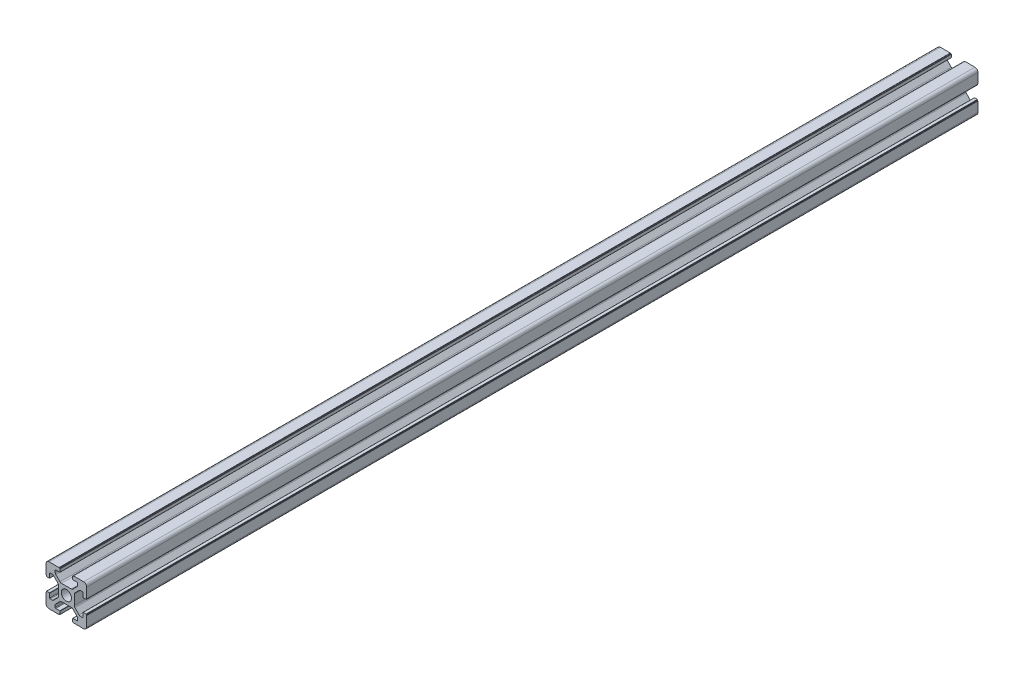
SolidWorks part; units mm, degrees
material "6063-T5"
ref_plane "前视基准面" through (0, 0, 0) normal (0, 0, 1) x (1, 0, 0)
ref_plane "上视基准面" through (0, 0, 0) normal (0, 1, 0) x (1, 0, 0)
ref_plane "右视基准面" through (0, 0, 0) normal (1, 0, 0) x (0, 0, -1)
sketch "草图1" plane through (0, 0, 0) normal (0, 0, 1) x (1, 0, 0)
  line L0 (-1.4389, 10) -> (24.3741, 10) construction
  line L1 (20, 13.6) -> (20, 20)
  line L2 (0, 0) -> (0, 6.4)
  line L3 (0, 20) -> (6.4, 20)
  line L4 (20, 0) -> (20, 6.4)
  line L5 (10, 21.5388) -> (10, -2.4017) construction
  line L6 (6.9, 18.3) -> (6.9, 19.7)
  line L7 (6.8, 18.2) -> (4.8, 18.2)
  line L8 (4.5, 17.9) -> (4.5, 16.9749)
  line L9 (4.7929, 16.2678) -> (6.8678, 14.1929)
  line L10 (7.5749, 13.9) -> (12.4251, 13.9)
  line L11 (6.8, 19.8) -> (6.4, 19.8)
  line L12 (6.4, 19.8) -> (6.4, 20)
  line L13 (0, 13.6) -> (0.2, 13.6)
  line L14 (0.2, 13.6) -> (0.2, 13.2)
  line L15 (0.3, 13.1) -> (1.7, 13.1)
  line L16 (1.8, 13.2) -> (1.8, 15.2)
  line L17 (2.1, 15.5) -> (3.0251, 15.5)
  line L18 (3.7322, 15.2071) -> (5.8071, 13.1322)
  line L19 (6.1, 12.4251) -> (6.1, 7.5749)
  line L20 (13.6, 19.8) -> (13.6, 20)
  line L21 (13.2, 19.8) -> (13.6, 19.8)
  line L22 (13.1, 18.3) -> (13.1, 19.7)
  line L23 (13.2, 18.2) -> (15.2, 18.2)
  line L24 (15.5, 17.9) -> (15.5, 16.9749)
  line L25 (15.2071, 16.2678) -> (13.1322, 14.1929)
  line L26 (0, 6.4) -> (0.2, 6.4)
  line L27 (0.2, 6.4) -> (0.2, 6.8)
  line L28 (0.3, 6.9) -> (1.7, 6.9)
  line L29 (1.8, 6.8) -> (1.8, 4.8)
  line L30 (2.1, 4.5) -> (3.0251, 4.5)
  line L31 (3.7322, 4.7929) -> (5.8071, 6.8678)
  line L32 (13.6, 20) -> (20, 20)
  line L33 (0, 13.6) -> (0, 20)
  line L34 (13.6, 0.2) -> (13.6, 0)
  line L35 (13.2, 0.2) -> (13.6, 0.2)
  line L36 (13.1, 1.7) -> (13.1, 0.3)
  line L37 (13.2, 1.8) -> (15.2, 1.8)
  line L38 (15.5, 2.1) -> (15.5, 3.0251)
  line L39 (15.2071, 3.7322) -> (13.1322, 5.8071)
  line L40 (4.5, 2.1) -> (4.5, 3.0251)
  line L41 (6.8, 1.8) -> (4.8, 1.8)
  line L42 (6.4, 0.2) -> (6.4, 0)
  line L43 (6.8, 0.2) -> (6.4, 0.2)
  line L44 (6.9, 1.7) -> (6.9, 0.3)
  line L45 (4.7929, 3.7322) -> (6.8678, 5.8071)
  line L46 (7.5749, 6.1) -> (12.4251, 6.1)
  line L47 (20, 6.4) -> (19.8, 6.4)
  line L48 (19.8, 6.4) -> (19.8, 6.8)
  line L49 (19.7, 6.9) -> (18.3, 6.9)
  line L50 (18.2, 6.8) -> (18.2, 4.8)
  line L51 (17.9, 4.5) -> (16.9749, 4.5)
  line L52 (16.2678, 4.7929) -> (14.1929, 6.8678)
  line L53 (13.9, 12.4251) -> (13.9, 7.5749)
  line L54 (16.2678, 15.2071) -> (14.1929, 13.1322)
  line L55 (17.9, 15.5) -> (16.9749, 15.5)
  line L56 (18.2, 13.2) -> (18.2, 15.2)
  line L57 (19.7, 13.1) -> (18.3, 13.1)
  line L58 (19.8, 13.6) -> (19.8, 13.2)
  line L59 (20, 13.6) -> (19.8, 13.6)
  line L60 (0, 0) -> (6.4, 0)
  line L61 (13.6, 0) -> (20, 0)
  arc A0 (6.1, 12.4251) -> (5.8071, 13.1322) centre (5.1, 12.4251) ccw
  arc A1 (7.5749, 13.9) -> (6.8678, 14.1929) centre (7.5749, 14.9) cw
  arc A2 (4.5, 16.9749) -> (4.7929, 16.2678) centre (5.5, 16.9749) ccw
  arc A3 (3.7322, 15.2071) -> (3.0251, 15.5) centre (3.0251, 14.5) ccw
  arc A4 (4.5, 17.9) -> (4.8, 18.2) centre (4.8, 17.9) cw
  arc A5 (1.8, 15.2) -> (2.1, 15.5) centre (2.1, 15.2) cw
  arc A6 (0.3, 13.1) -> (0.2, 13.2) centre (0.3, 13.2) cw
  arc A7 (6.9, 19.7) -> (6.8, 19.8) centre (6.8, 19.7) ccw
  arc A8 (1.7, 13.1) -> (1.8, 13.2) centre (1.7, 13.2) ccw
  arc A9 (6.9, 18.3) -> (6.8, 18.2) centre (6.8, 18.3) cw
  arc A10 (13.1, 19.7) -> (13.2, 19.8) centre (13.2, 19.7) cw
  arc A11 (13.1, 18.3) -> (13.2, 18.2) centre (13.2, 18.3) ccw
  arc A12 (15.5, 17.9) -> (15.2, 18.2) centre (15.2, 17.9) ccw
  arc A13 (15.5, 16.9749) -> (15.2071, 16.2678) centre (14.5, 16.9749) cw
  arc A14 (12.4251, 13.9) -> (13.1322, 14.1929) centre (12.4251, 14.9) ccw
  arc A15 (0.3, 6.9) -> (0.2, 6.8) centre (0.3, 6.8) ccw
  arc A16 (1.7, 6.9) -> (1.8, 6.8) centre (1.7, 6.8) cw
  arc A17 (1.8, 4.8) -> (2.1, 4.5) centre (2.1, 4.8) ccw
  arc A18 (3.7322, 4.7929) -> (3.0251, 4.5) centre (3.0251, 5.5) cw
  arc A19 (6.1, 7.5749) -> (5.8071, 6.8678) centre (5.1, 7.5749) cw
  arc A20 (13.1, 0.3) -> (13.2, 0.2) centre (13.2, 0.3) ccw
  arc A21 (13.1, 1.7) -> (13.2, 1.8) centre (13.2, 1.7) cw
  arc A22 (15.5, 2.1) -> (15.2, 1.8) centre (15.2, 2.1) cw
  arc A23 (15.5, 3.0251) -> (15.2071, 3.7322) centre (14.5, 3.0251) ccw
  arc A24 (12.4251, 6.1) -> (13.1322, 5.8071) centre (12.4251, 5.1) cw
  arc A25 (4.5, 2.1) -> (4.8, 1.8) centre (4.8, 2.1) ccw
  arc A26 (6.9, 0.3) -> (6.8, 0.2) centre (6.8, 0.3) cw
  arc A27 (6.9, 1.7) -> (6.8, 1.8) centre (6.8, 1.7) ccw
  arc A28 (4.5, 3.0251) -> (4.7929, 3.7322) centre (5.5, 3.0251) cw
  arc A29 (7.5749, 6.1) -> (6.8678, 5.8071) centre (7.5749, 5.1) ccw
  arc A30 (19.7, 6.9) -> (19.8, 6.8) centre (19.7, 6.8) cw
  arc A31 (18.3, 6.9) -> (18.2, 6.8) centre (18.3, 6.8) ccw
  arc A32 (18.2, 4.8) -> (17.9, 4.5) centre (17.9, 4.8) cw
  arc A33 (16.2678, 4.7929) -> (16.9749, 4.5) centre (16.9749, 5.5) ccw
  arc A34 (13.9, 7.5749) -> (14.1929, 6.8678) centre (14.9, 7.5749) ccw
  arc A35 (13.9, 12.4251) -> (14.1929, 13.1322) centre (14.9, 12.4251) cw
  arc A36 (16.2678, 15.2071) -> (16.9749, 15.5) centre (16.9749, 14.5) cw
  arc A37 (18.2, 15.2) -> (17.9, 15.5) centre (17.9, 15.2) ccw
  arc A38 (18.3, 13.1) -> (18.2, 13.2) centre (18.3, 13.2) cw
  arc A39 (19.7, 13.1) -> (19.8, 13.2) centre (19.7, 13.2) ccw
  circle A40 centre (10, 10) radius 2.5
  point P39 (0.2, 13.1)
  point P42 (6.9, 19.8)
  point P45 (1.8, 13.1)
  point P48 (6.9, 18.2)
  point P66 (10, 13.9)
  point P83 (6.1, 10)
  dimension "D19" = 1
  dimension "D20" = 1
  dimension "D21" = 0.3
  dimension "D22" = 0.1
  dimension "D23" = 5
  dimension "D1" = 20
  dimension "D2" = 20
  dimension "D3" = 10
  dimension "D4" = 10
  dimension "D5" = 1.8
  dimension "D6" = 0.5
  dimension "D7" = 1.6
  dimension "D8" = 3.1
  dimension "D9" = 6.1
  dimension "D10" = 5.5
  dimension "D11" = 3.1
  dimension "D12" = 6.1
  dimension "D13" = 5.5
  dimension "D14" = 1.8
  dimension "D15" = 0.5
  dimension "D16" = 1.5
  dimension "D17" = 45
  dimension "D18" = 1.6
extrude "凸台-拉伸1" add sketch "草图1" along normal blind 438
fillet "圆角1" radius 1.5 4 edges at (20, 0, 219) (0, 0, 219) (0, 20, 219) (20, 20, 219)
